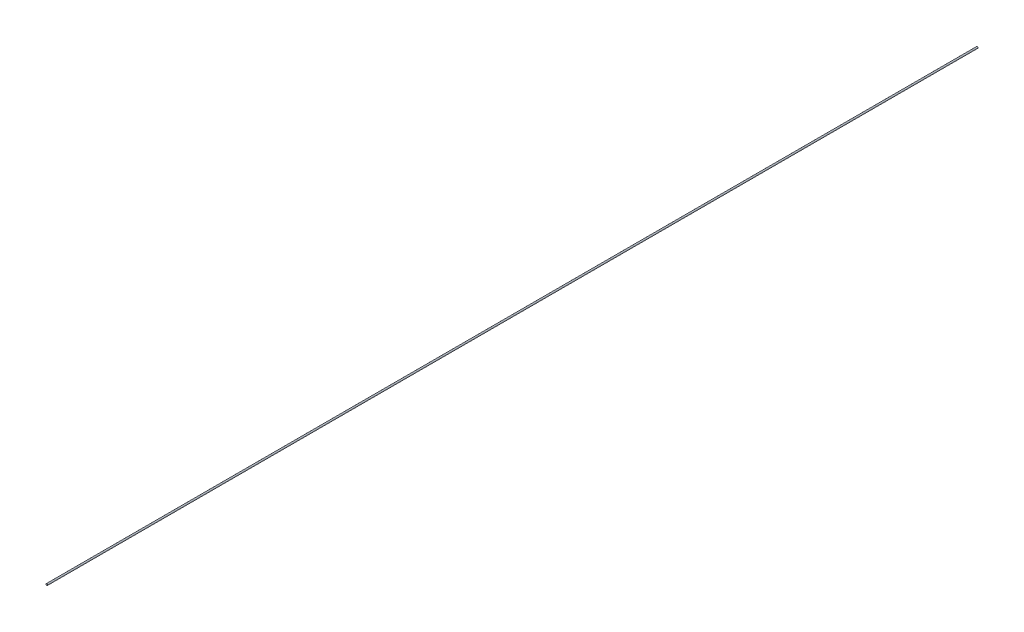
SolidWorks part; units mm, degrees
material "Plain Carbon Steel"
ref_plane "Front Plane" through (0, 0, 0) normal (0, 0, 1) x (1, 0, 0)
ref_plane "Top Plane" through (0, 0, 0) normal (0, 1, 0) x (1, 0, 0)
ref_plane "Right Plane" through (0, 0, 0) normal (1, 0, 0) x (0, 0, -1)
sketch "Sketch1" plane through (0, 0, 0) normal (0, 0, 1) x (1, 0, 0)
  circle A1 centre (0, 0) radius 0.33
  dimension "D1" = 0.66
extrude "Boss-Extrude1" add sketch "Sketch1" along normal blind 400
